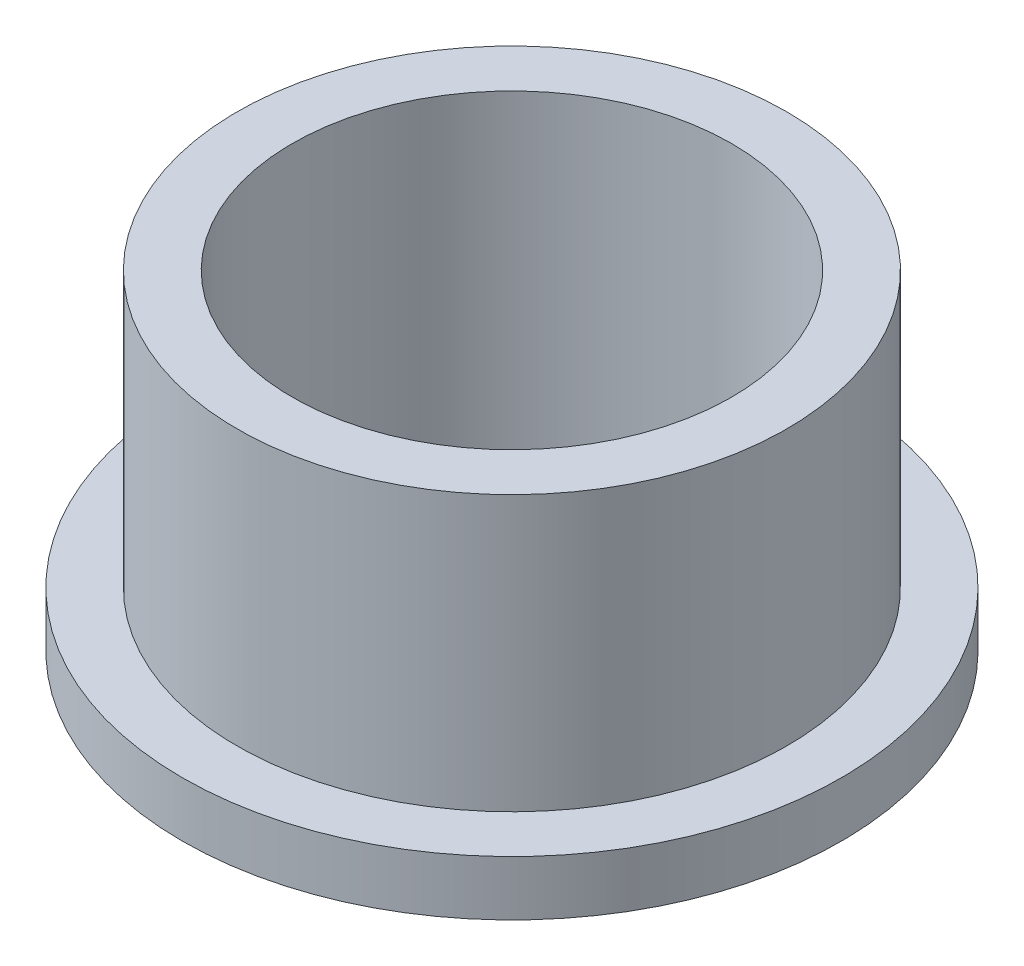
SolidWorks part; units mm, degrees
ref_plane "Front" through (0, 0, 0) normal (0, 0, 1) x (1, 0, 0)
ref_plane "Top" through (0, 0, 0) normal (0, 1, 0) x (1, 0, 0)
ref_plane "Right" through (0, 0, 0) normal (1, 0, 0) x (0, 0, -1)
sketch "Sketch1" plane through (0, 0, 0) normal (0, 1, 0) x (1, 0, 0)
  circle A0 centre (0, 0) radius 12.7
  circle A1 centre (0, 0) radius 15.8813
  circle A2 centre (0, 0) radius 19.05
  dimension "ID" = 25.4
  dimension "OD" = 31.7627
  dimension "FlangeOD" = 38.1
sketch "Sketch2" plane through (0, 0, 0) normal (0, 1, 0) x (1, 0, 0)
  circle A0 centre (0, 0) radius 12.7 construction
  circle A1 centre (0, 0) radius 15.8813 construction
  circle A2 centre (0, 0) radius 12.7
  circle A3 centre (0, 0) radius 15.8813
extrude "Boss-Extrude1" add sketch "Sketch2" along normal blind 19.05
sketch "Sketch3" plane through (0, 0, 0) normal (0, 1, 0) x (1, 0, 0)
  circle A0 centre (0, 0) radius 19.05 construction
  circle A1 centre (0, 0) radius 15.8813 construction
  circle A2 centre (0, 0) radius 19.05
  circle A3 centre (0, 0) radius 15.8813
extrude "Boss-Extrude2" add sketch "Sketch3" along normal blind 3.175
